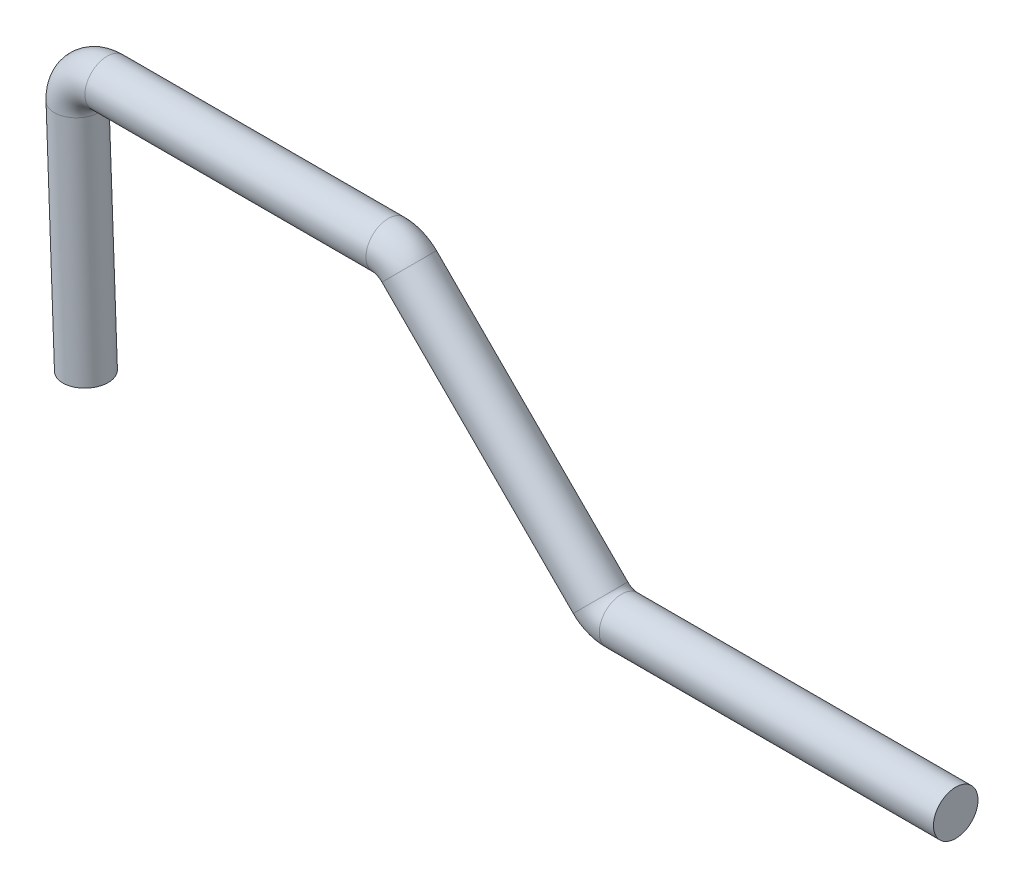
SolidWorks part; units mm, degrees
ref_plane "Front Plane" through (0, 0, 0) normal (0, 0, 1) x (1, 0, 0)
ref_plane "Top Plane" through (0, 0, 0) normal (0, 1, 0) x (1, 0, 0)
ref_plane "Right Plane" through (0, 0, 0) normal (1, 0, 0) x (0, 0, -1)
sketch "Sketch1" plane through (0, 0, 0) normal (1, 0, 0) x (0, 0, -1)
  circle A0 centre (0, 0) radius 7.5
  dimension "D1" = 15
sketch3d "3DSketch1"
  line L0 (0, 0, 0) -> (-112.5521, 0, 0)
  line L1 (-119.6231, 2.9289, 0) -> (-184.0395, 67.3453, 0)
  line L2 (-191.1106, 70.2742, 0) -> (-285.7768, 70.2742, 0)
  line L3 (-295.77, 59.9048, 0) -> (-292.9081, -17.508, 0)
  arc A0 (-112.5521, 0, 0) -> (-119.6231, 2.9289, 0) centre (-112.5521, 10, 0) ccw
  arc A1 (-285.7768, 70.2742, 0) -> (-295.77, 59.9048, 0) centre (-285.7768, 60.2742, 0) ccw
  arc A2 (-184.0395, 67.3453, 0) -> (-191.1106, 70.2742, 0) centre (-191.1106, 60.2742, 0) ccw
  point P8 (-116.6942, 0, 0)
  point P9 (-112.5521, 10, -10)
  point P12 (-296.1533, 70.2742, 0)
  point P13 (-285.7768, 60.2742, 10)
  point P16 (-186.9684, 70.2742, 0)
  point P17 (-191.1106, 60.2742, 10)
  dimension "D1" = 10
sweep "Sweep3" add profiles "Sketch1" path "3DSketch1"
